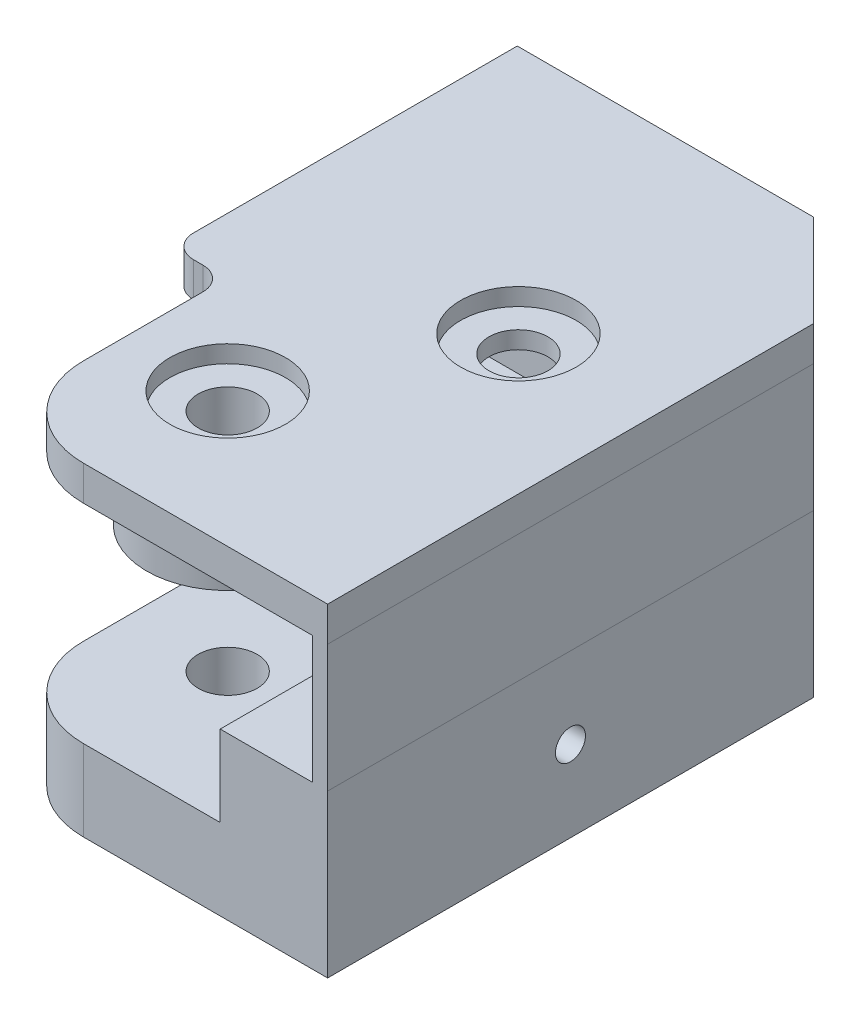
SolidWorks part; units mm, degrees
ref_plane "Front" through (0, 0, 0) normal (0, 0, 1) x (1, 0, 0)
ref_plane "Top" through (0, 0, 0) normal (0, 1, 0) x (1, 0, 0)
ref_plane "Right" through (0, 0, 0) normal (1, 0, 0) x (0, 0, -1)
sketch "Эскиз1" plane through (0, 0, 0) normal (0, 1, 0) x (1, 0, 0)
  line L0 (8.8, 25) -> (-16.8, 25)
  line L1 (16.8, 17) -> (8.8, 25)
  line L2 (16.8, -25) -> (16.8, 17)
  line L3 (-16.8, 25) -> (-16.8, -3)
  line L4 (-14.8, -5) -> (-13.9793, -5)
  line L5 (-11.9793, -7) -> (-11.9793, -23)
  line L6 (-9.9793, -25) -> (16.8, -25)
  circle A1 centre (4.8, 3.5) radius 2.55
  circle A2 centre (-3.4895, -13.3528) radius 2.55
  arc A3 (-11.9793, -23) -> (-9.9793, -25) centre (-9.9793, -23) ccw
  arc A4 (-16.8, -3) -> (-14.8, -5) centre (-14.8, -3) ccw
  arc A5 (-13.9793, -5) -> (-11.9793, -7) centre (-13.9793, -7) cw
extrude "Бобышка-Вытянуть1" add sketch "Эскиз1" along normal blind 7
sketch "Эскиз3" plane through (0, 7, 0) normal (0, 1, 0) x (1, 0, 0)
  line L7 (8.8, 25) -> (-16.8, 25)
  line L8 (16.8, 17) -> (8.8, 25)
  line L9 (16.8, -25) -> (16.8, 17)
  line L10 (-16.8, 25) -> (-16.8, -2.3528)
  line L13 (7.5105, -25) -> (16.8, -25)
  line L21 (-3.4895, -2.3528) -> (-16.8, -2.3528)
  line L22 (7.5105, -13.3528) -> (7.5105, -25)
  circle A7 centre (4.8, 3.5) radius 2.55
  arc A11 (7.5105, -13.3528) -> (-3.4895, -2.3528) centre (-3.4895, -13.3528) ccw
extrude "Бобышка-Вытянуть2" add sketch "Эскиз3" along normal blind 7
sketch "Эскиз4" plane through (0, 14, 0) normal (0, 1, 0) x (1, 0, 0)
  line L7 (8.8, 25) -> (-16.8, 25)
  line L8 (16.8, 17) -> (8.8, 25)
  line L9 (16.8, -25) -> (16.8, 17)
  line L10 (-16.8, 25) -> (-16.8, 14.5)
  line L13 (15.5, -25) -> (16.8, -25)
  line L20 (4.8, 14.5) -> (-16.8, 14.5)
  line L21 (15.5, -25) -> (15.5, 0.9486)
  arc A8 (15.5, 0.9486) -> (4.8, 14.5) centre (4.8, 3.5) ccw
  dimension "D1" = 1.3
extrude "Бобышка-Вытянуть3" add sketch "Эскиз4" along normal blind 11
sketch "Эскиз5" plane through (0, 25, 0) normal (0, 1, 0) x (1, 0, 0)
  line L7 (8.8, 25) -> (-16.8, 25)
  line L8 (16.8, 17) -> (8.8, 25)
  line L9 (16.8, -25) -> (16.8, 17)
  line L10 (-16.8, 25) -> (-16.8, -3)
  line L11 (-14.8, -5) -> (-13.9793, -5)
  line L12 (-11.9793, -7) -> (-11.9793, -17.3431)
  line L13 (-4.3224, -25) -> (16.8, -25)
  circle A7 centre (4.8, 3.5) radius 2.55
  circle A8 centre (-3.4895, -13.3528) radius 2.55
  arc A10 (-16.8, -3) -> (-14.8, -5) centre (-14.8, -3) ccw
  arc A11 (-13.9793, -5) -> (-11.9793, -7) centre (-13.9793, -7) cw
  arc A12 (-11.9793, -17.3431) -> (-4.3224, -25) centre (-4.3224, -17.3431) ccw
extrude "Бобышка-Вытянуть4" add sketch "Эскиз5" along normal blind 3
sketch "Эскиз6" plane through (0, 25, 0) normal (0, -1, 0) x (1, 0, 0)
  circle A0 centre (-3.4895, 13.3528) radius 2.55
  circle A1 centre (-3.4895, 13.3528) radius 7
extrude "Бобышка-Вытянуть5" add sketch "Эскиз6" along normal blind 7
sketch "Эскиз7" plane through (0, 0, -25) normal (0, 0, -1) x (-1, 0, 0)
  circle A0 centre (4, 13.75) radius 1.3
extrude "Вырез-Вытянуть1" cut sketch "Эскиз7" against normal blind 5
sketch "Эскиз8" plane through (16.8, 0, 0) normal (1, 0, 0) x (0, 0, -1)
  line L0 (-25, 0) -> (17, 0) construction
  circle A0 centre (-4, 7) radius 1.3
  point P5 (-4, 0)
  dimension "D1" = 7
extrude "Вырез-Вытянуть2" cut sketch "Эскиз8" against normal blind 5
sketch "Эскиз9" plane through (0, 28, 0) normal (0, 1, 0) x (1, 0, 0)
  circle A0 centre (4.8, 3.5) radius 5
  circle A1 centre (-3.4895, -13.3528) radius 5
extrude "Вырез-Вытянуть3" cut sketch "Эскиз9" against normal blind 1.5
sketch "Эскиз11" plane through (0, 7, 0) normal (0, 1, 0) x (1, 0, 0)
  line L0 (-11.9793, -17.3431) -> (-11.9793, -25)
  line L1 (-11.9793, -25) -> (-4.3224, -25)
  arc A0 (-11.9793, -17.3431) -> (-4.3224, -25) centre (-4.3224, -17.3431) ccw
extrude "Вырез-Вытянуть4" cut sketch "Эскиз11" against normal up to next
fillet "Скругление1" radius 2 1 edges at (-3.4895, 25, 20.3528)
